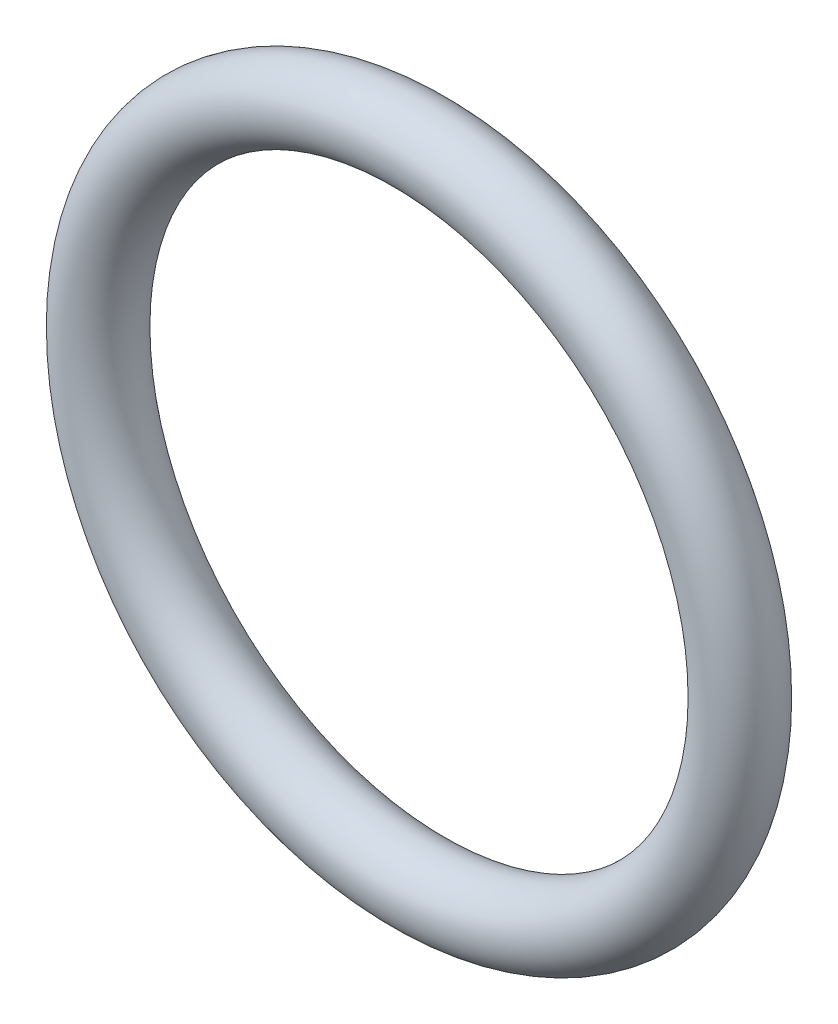
SolidWorks part; units mm, degrees
ref_plane "Front" through (0, 0, 0) normal (0, 0, 1) x (1, 0, 0)
ref_plane "Top" through (0, 0, 0) normal (0, 1, 0) x (1, 0, 0)
ref_plane "Right" through (0, 0, 0) normal (1, 0, 0) x (0, 0, -1)
sketch "Sketch1" plane through (0, 0, 0) normal (1, 0, 0) x (0, -1, 0)
  line L0 (0, -1.3081) -> (0, 1.3081) construction
  line L2 (-14.0399, 0) -> (14.0399, 0) construction
  line L3 (-10.1473, 0) -> (10.1473, 0) construction
  circle A0 centre (11.4554, 0) radius 1.3081
  point P9 (10.1473, 0)
  point P10 (12.7635, 0)
  point P13 (11.4554, 1.3081)
  point P14 (11.4554, -1.3081)
  dimension "Width" = 2.6162
  dimension "ID" = 20.2946
revolve "Revolve1" add sketch "Sketch1" angle 360 about L0
